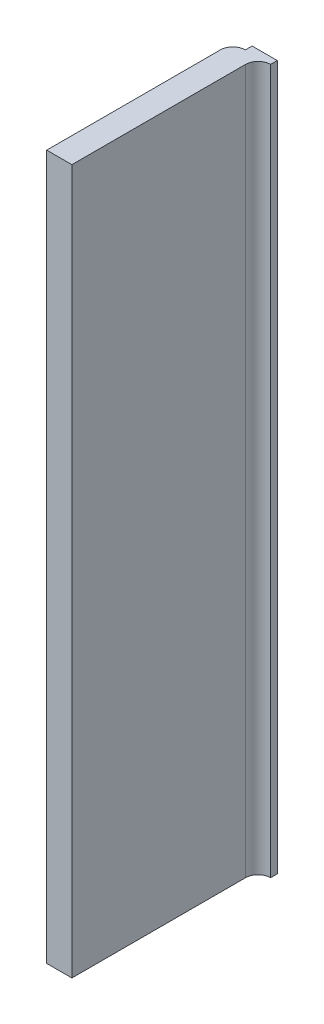
SolidWorks part; units mm, degrees
ref_plane "Front Plane" through (0, 0, 0) normal (0, 0, 1) x (1, 0, 0)
ref_plane "Top Plane" through (0, 0, 0) normal (0, 1, 0) x (1, 0, 0)
ref_plane "Right Plane" through (0, 0, 0) normal (1, 0, 0) x (0, 0, -1)
sketch "Sketch1" plane through (0, 0, 0) normal (0, 1, 0) x (1, 0, 0)
  line L0 (2.8291, 4.5665) -> (5.8145, 4.5665)
  line L1 (5.8145, 2.9665) -> (5.8145, 4.5665)
  line L2 (-3.1709, 4.5665) -> (2.8291, 4.5665)
  line L3 (-3.1709, 4.5665) -> (-3.1709, -41.4335)
  line L4 (-3.1709, -41.4335) -> (2.8291, -41.4335)
  line L5 (2.8291, 4.5665) -> (2.8291, -41.4335)
  line L6 (5.8145, 7.1391) -> (5.8145, -13.1512) construction
  line L8 (-0.1855, 2.9665) -> (-0.1855, 4.5665)
  arc A1 (5.8145, 2.9665) -> (2.8291, -0.0188) centre (5.8145, -0.0188) ccw
  arc A2 (-0.1855, 2.9665) -> (-3.1709, -0.0188) centre (-0.1855, -0.0188) ccw
  dimension "D2" = 1.6
  dimension "D3" = 6
  dimension "D1" = 46
  dimension "D4" = 1.6
extrude "Boss-Extrude1" add sketch "Sketch1" along normal blind 168 contours A1 L1 L0 L5 | L8 A2 L3 L4 L5 L2
sketch "Sketch2" plane through (-3.1709, 0, 0) normal (-1, 0, 0) x (0, 0, 1)
  line L0 (41.4335, 84) -> (-36.3885, 84) construction
  line L1 (41.4335, 168) -> (41.4335, 0) construction
  line L3 (0.0188, 168) -> (41.4335, 168) construction
  circle A0 centre (19.8335, 142.3) radius 19
  dimension "D1" = 2.6
  dimension "D2" = 6.7
